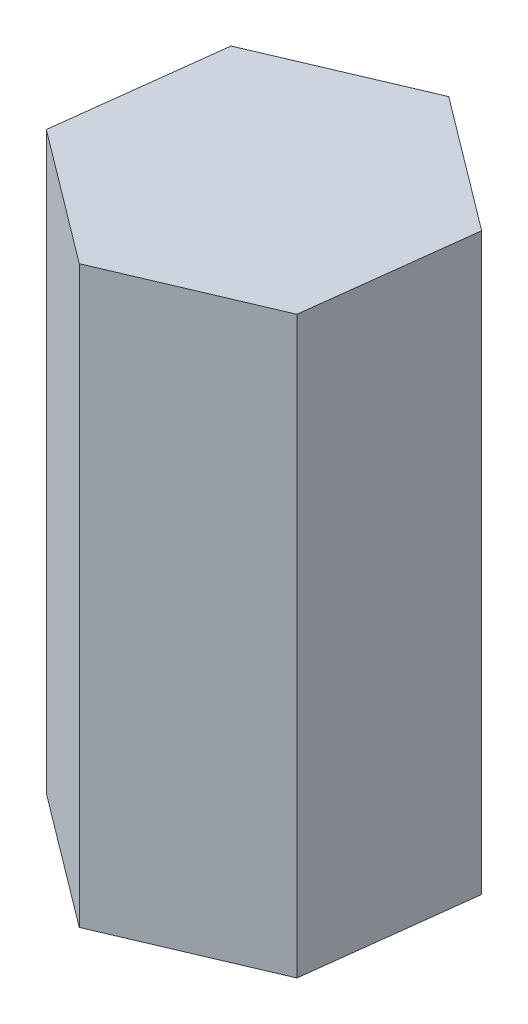
SolidWorks part; units mm, degrees
ref_plane "Front Plane" through (0, 0, 0) normal (0, 0, 1) x (1, 0, 0)
ref_plane "Top Plane" through (0, 0, 0) normal (0, 1, 0) x (1, 0, 0)
ref_plane "Right Plane" through (0, 0, 0) normal (1, 0, 0) x (0, 0, -1)
sketch "Sketch1" plane through (0, 0, 0) normal (0, 1, 0) x (1, 0, 0)
  line L5 (2.3075, -1.7346) -> (2.6559, 1.131)
  line L6 (2.6559, 1.131) -> (0.3485, 2.8656)
  line L7 (0.3485, 2.8656) -> (-2.3075, 1.7346)
  line L8 (-2.3075, 1.7346) -> (-2.6559, -1.131)
  line L9 (-2.6559, -1.131) -> (-0.3485, -2.8656)
  line L10 (-0.3485, -2.8656) -> (2.3075, -1.7346)
  circle A0 centre (0, 0) radius 2.5 construction
extrude "Boss-Extrude1" add sketch "Sketch1" along normal blind 10
